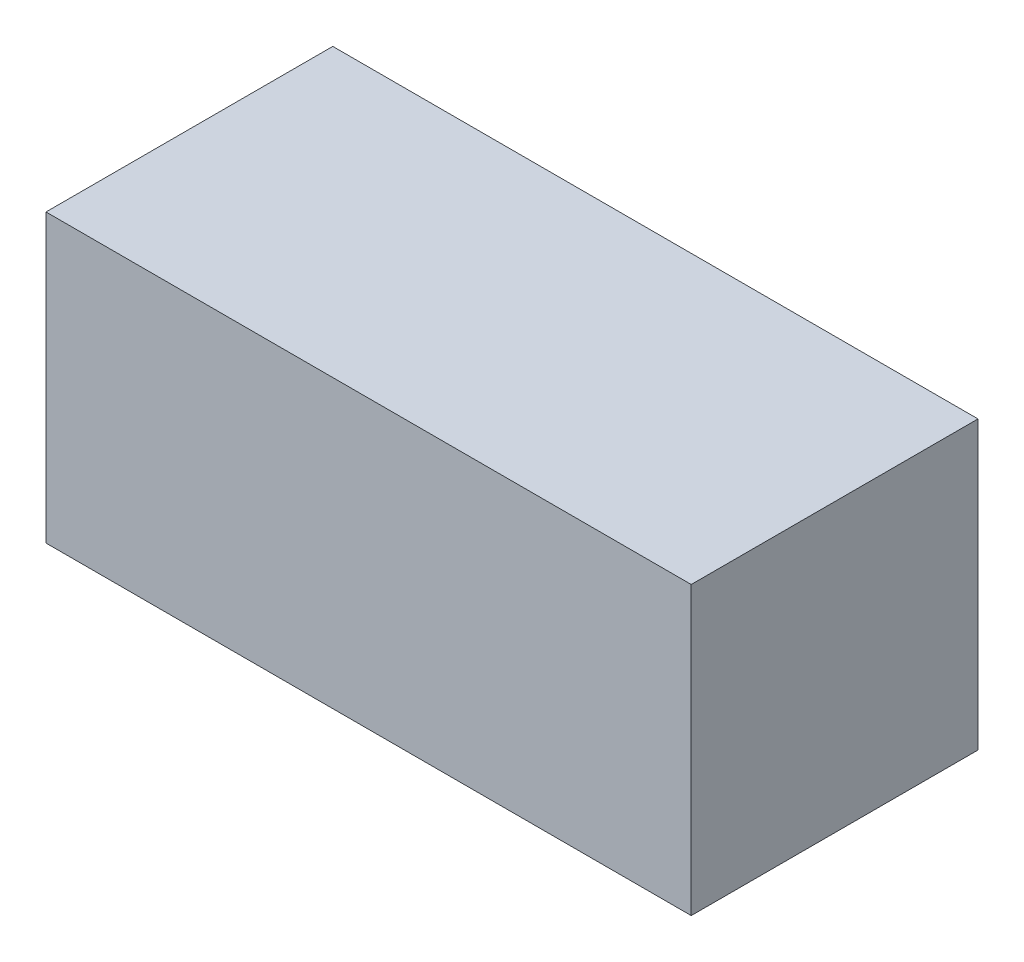
SolidWorks part; units mm, degrees
ref_plane "Front Plane" through (0, 0, 0) normal (0, 0, 1) x (1, 0, 0)
ref_plane "Top Plane" through (0, 0, 0) normal (0, 1, 0) x (1, 0, 0)
ref_plane "Right Plane" through (0, 0, 0) normal (1, 0, 0) x (0, 0, -1)
sketch "Sketch2" plane through (0, 0, 0) normal (0, 1, 0) x (1, 0, 0)
  line L1 (0, 0) -> (-457.2, 0)
  line L2 (0, 0) -> (0, 203.2)
  line L3 (0, 203.2) -> (-457.2, 203.2)
  line L4 (-457.2, 0) -> (-457.2, 203.2)
extrude "Boss-Extrude1" add sketch "Sketch2" along normal blind 203.2
